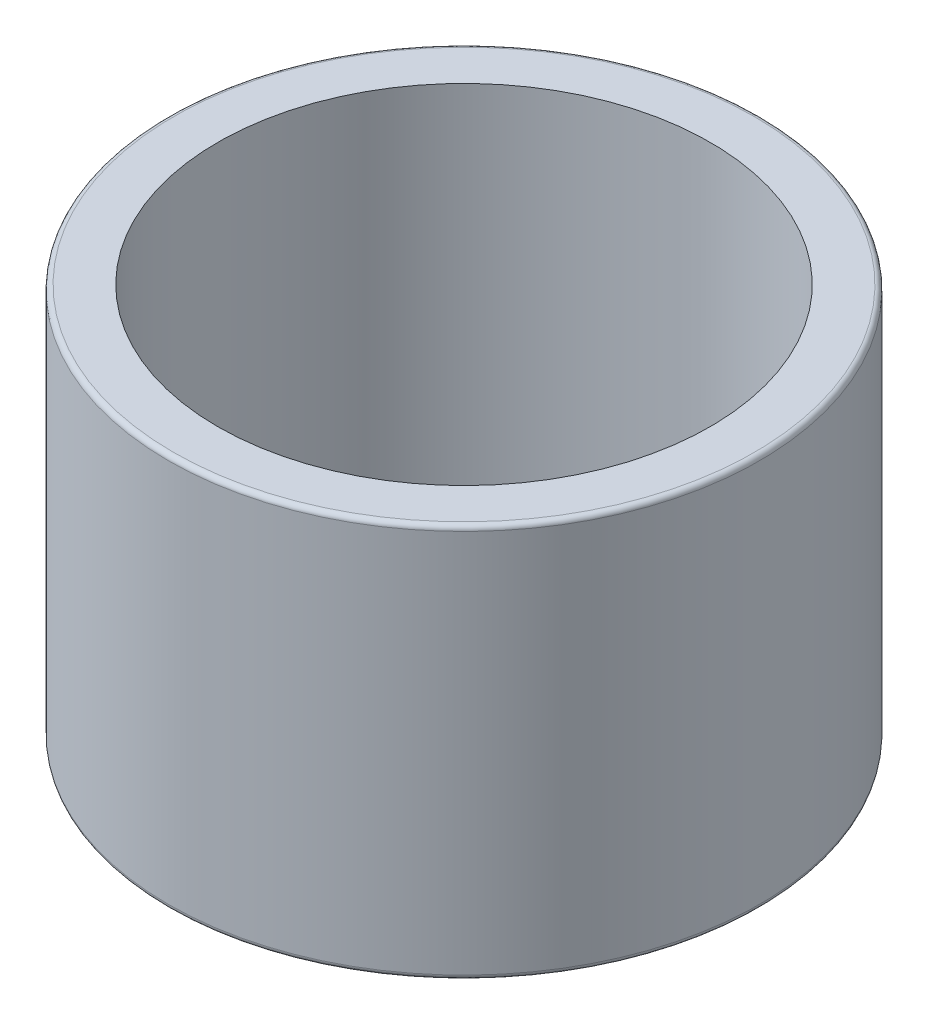
SolidWorks part; units mm, degrees
material "ABS"
ref_plane "Ebene vorne" through (0, 0, 0) normal (0, 0, 1) x (1, 0, 0)
ref_plane "Ebene oben" through (0, 0, 0) normal (0, 1, 0) x (1, 0, 0)
ref_plane "Ebene rechts" through (0, 0, 0) normal (1, 0, 0) x (0, 0, -1)
sketch "Skizze1" plane through (0, 0, 0) normal (0, 1, 0) x (1, 0, 0)
  circle A0 centre (0, 0) radius 5
  circle A1 centre (0, 0) radius 6
  dimension "D1" = 10
  dimension "D2" = 1
extrude "Aufsatz-Linear austragen1" add sketch "Skizze1" along normal mid plane 8
fillet "Verrundung1" radius 0.1 2 edges at (0, -4, 6) (0, 4, 6)
